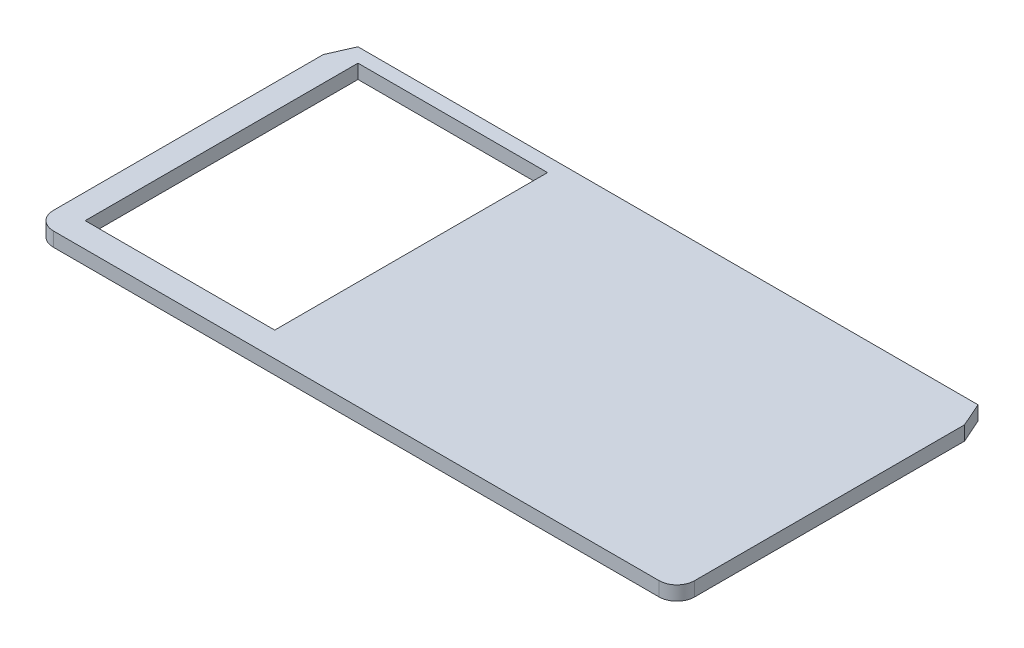
SolidWorks part; units mm, degrees
ref_plane "Front Plane" through (0, 0, 0) normal (0, 0, 1) x (1, 0, 0)
ref_plane "Top Plane" through (0, 0, 0) normal (0, 1, 0) x (1, 0, 0)
ref_plane "Right Plane" through (0, 0, 0) normal (1, 0, 0) x (0, 0, -1)
sketch "Sketch1" plane through (0, 0, 0) normal (0, 1, 0) x (1, 0, 0)
  line L1 (-87.5, -42.5) -> (87.5, -42.5)
  line L2 (-87.5, -42.5) -> (-87.5, 42.5)
  line L3 (-87.5, 42.5) -> (87.5, 42.5)
  line L4 (87.5, -42.5) -> (87.5, 42.5)
  line L5 (-87.5, -42.5) -> (87.5, 42.5) construction
  line L6 (-87.5, 42.5) -> (87.5, -42.5) construction
  line L7 (-90.5, 35.7) -> (-90.5, -40.5)
  line L8 (-85.5, -45.5) -> (85.5, -45.5)
  line L9 (90.5, -40.5) -> (90.5, 35.7)
  line L11 (-87.5, -42.5) -> (-87.5, 35.7)
  line L13 (-90.5, 35.7) -> (-87.5, 42.5)
  line L14 (87.5, -42.5) -> (87.5, 35.7)
  line L16 (90.5, 35.7) -> (87.5, 42.5)
  line L18 (30, -38.0115) -> (83.5, 40.5571) construction
  line L19 (30, 40.5571) -> (83.5, -38.0115) construction
  line L20 (-83.5, -38.5) -> (-30, -38.5)
  line L21 (-83.5, -38.5) -> (-83.5, 38.5)
  line L22 (-83.5, 38.5) -> (-30, 38.5)
  line L23 (-30, -38.5) -> (-30, 38.5)
  line L24 (-83.5, -38.5) -> (-30, 38.5) construction
  line L25 (-83.5, 38.5) -> (-30, -38.5) construction
  arc A0 (85.5, -45.5) -> (90.5, -40.5) centre (85.5, -40.5) ccw
  arc A1 (-90.5, -40.5) -> (-85.5, -45.5) centre (-85.5, -40.5) ccw
  point P0 (0, 0)
  point P7 (56.75, 1.2728)
  point P14 (-35.306, -60.4181)
  point P23 (-56.75, 0)
  dimension "D3" = 5
  dimension "D1" = 85
  dimension "D2" = 175
  dimension "D6" = 4
  dimension "D7" = 30
  dimension "D8" = 4
  dimension "D9" = 4
extrude "Boss-Extrude1" add sketch "Sketch1" along normal blind 4 contours L7 A1 L8 A0 L9 L16 L4 L1 L2 L13 | L1 L4 L3 L2
sketch "Sketch2" plane through (0, 0, 0) normal (0, 1, 0) x (1, 0, 0)
  line L1 (-20, -10) -> (20, -10)
  line L2 (-20, -10) -> (-20, 10)
  line L3 (-20, 10) -> (20, 10)
  line L4 (20, -10) -> (20, 10)
  line L5 (-20, -10) -> (20, 10) construction
  line L6 (-20, 10) -> (20, -10) construction
  point P1 (0, 0)
  dimension "D1" = 40
  dimension "D2" = 20
extrude "Boss-Extrude2" add sketch "Sketch2" against normal blind 2
ref_plane "Plane1" through (0, -2, 0) normal (0, 1, 0) x (1, 0, 0)
sketch "Sketch3" plane through (0, -2, 0) normal (0, 1, 0) x (1, 0, 0)
  line L0 (0, 9) -> (2, 9)
  line L1 (-17.5, -9) -> (17.5, -9)
  line L2 (-17.5, -9) -> (-17.5, 9)
  line L3 (-17.5, 9) -> (17.5, 9)
  line L4 (17.5, -9) -> (17.5, 9)
  line L5 (-17.5, -9) -> (17.5, 9) construction
  line L6 (-17.5, 9) -> (17.5, -9) construction
  line L7 (0, 9) -> (-2, 9)
  line L8 (17.5, 0) -> (17.5, 2)
  line L9 (17.5, 0) -> (17.5, -2)
  line L10 (0, -9) -> (2, -9)
  line L11 (0, -9) -> (-2, -9)
  line L12 (-17.5, 0) -> (-17.5, 2)
  line L13 (-17.5, 0) -> (-17.5, -2)
  line L14 (-17.5, 2) -> (-2, 9)
  line L15 (2, 9) -> (17.5, 2)
  line L16 (17.5, -2) -> (2, -9)
  line L17 (-2, -9) -> (-17.5, -2)
  line L19 (-20, -10) -> (20, -10)
  line L20 (-20, -10) -> (-20, 10)
  line L21 (-20, 10) -> (20, 10)
  line L22 (20, -10) -> (20, 10)
  line L23 (-20, -10) -> (20, 10) construction
  line L24 (-20, 10) -> (20, -10) construction
  point P0 (0, 0)
  point P17 (0, 0)
  dimension "D1" = 18
  dimension "D2" = 35
  dimension "D3" = 20
  dimension "D4" = 40
extrude "Boss-Extrude3" add sketch "Sketch3" against normal blind 4 contours L2 L14 L3 | L19 L22 L21 L20 L4 L1 L2 L3 L0 | L1 L17 L2 | L4 L16 L1 | L3 L15 L4
